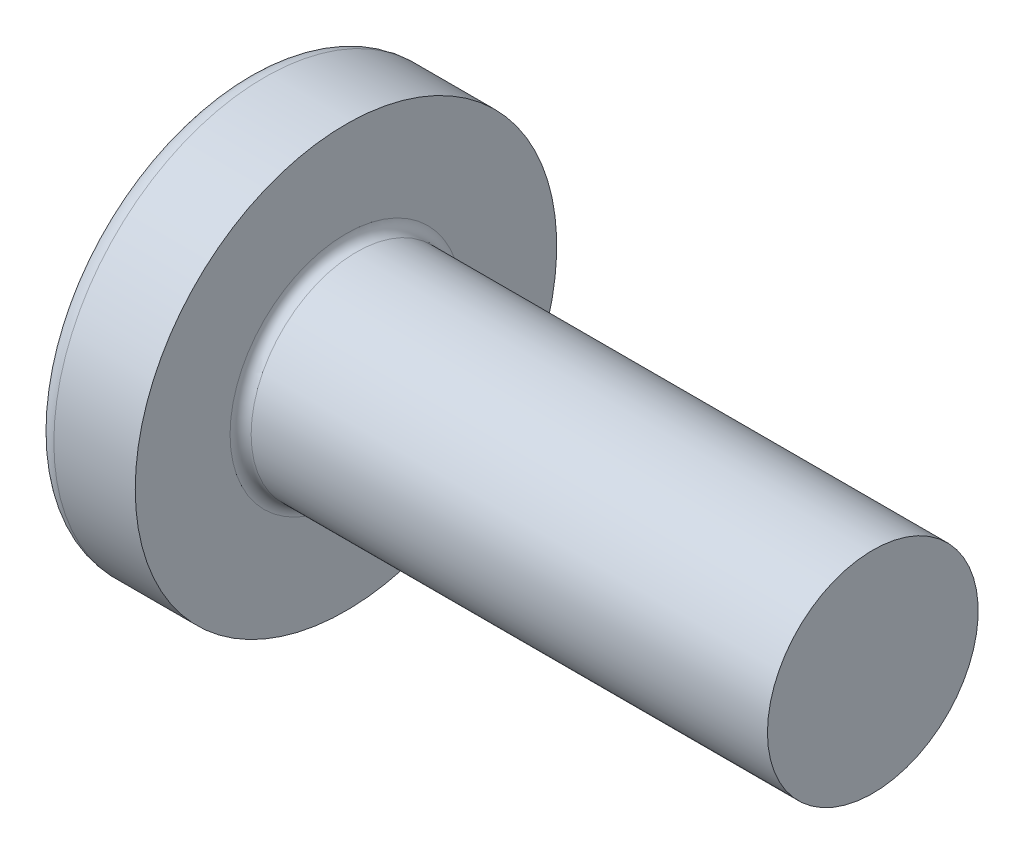
SolidWorks part; units mm, degrees
ref_plane "Plane1" through (0, 0, 0) normal (0, 0, 1) x (1, 0, 0)
ref_plane "Plane2" through (0, 0, 0) normal (0, 1, 0) x (1, 0, 0)
ref_plane "Plane3" through (0, 0, 0) normal (1, 0, 0) x (0, 0, -1)
sketch "BodySke" plane through (0, 0, 0) normal (0, 0, 1) x (1, 0, 0)
  line L0 (3.1, 2) -> (3.1, 4)
  line L1 (3.45, 6.35) -> (3.45, -3.175) construction
  line L2 (-25.4, 0) -> (127, 0) construction
  line L3 (13.1, 0) -> (0, 0)
  line L4 (3.1, 2) -> (13.1, 2)
  line L5 (13.1, 2) -> (13.1, 0)
  line L6 (1.5553, 4) -> (3.1, 4)
  line L8 (3.1, 6.35) -> (3.1, -3.175) construction
  arc A0 (1.2654, 3.8534) -> (0, 0) centre (6.5, 0) ccw
  arc A2 (1.2654, 3.8534) -> (1.5553, 4) centre (1.5553, 3.64) cw
  dimension "Head_crown_rad" = 6.5
  dimension "Head_fillet_rad" = 0.36
  dimension "Length" = 10
  dimension "Head_ht" = 3.1
  dimension "Head_dia" = 8
  dimension "Advance" = 0.7
  dimension "Thread_nom" = 10
  dimension "Diameter" = 4
revolve "Base-Revolve" add sketch "BodySke"
cosmetic thread "ThreadCosmetic"
fillet "Fillet1" radius 0.2 1 edges at (3.1, 0, 2)
sketch "Sketch3" plane through (0, 0, 0) normal (1, 0, 0) x (0, 0, -1)
  line L0 (0.515, -2.15) -> (-0.515, -2.15)
  line L1 (0.515, -2.15) -> (0.515, 2.15)
  line L2 (-0.515, 2.15) -> (0.515, 2.15)
  line L3 (-0.515, 2.15) -> (-0.515, -2.15)
  dimension "Cross_dia" = 4.3
  dimension "D1" = 2.15
  dimension "Cross_width" = 1.03
  dimension "D2" = 0.515
ref_plane "Plane4" through (2.34, 0, 0) normal (1, 0, 0) x (0, 0, -1)
sketch "Sketch4" plane through (2.34, 0, 0) normal (1, 0, 0) x (0, 0, -1)
  line L0 (0.515, -0.9833) -> (-0.515, -0.9833)
  line L1 (0.515, -0.9833) -> (0.515, 0.9833)
  line L2 (-0.515, 0.9833) -> (0.515, 0.9833)
  line L3 (-0.515, 0.9833) -> (-0.515, -0.9833)
  dimension "D1" = 1.03
  dimension "D2" = 1.9666
  dimension "D3" = 0.515
  dimension "D4" = 0.9833
loft "Recess" cut profiles "Sketch3", "Sketch4"
pattern_circular "RecPat" count 2 every 90 about axis through (0, 0, 0) along (1, 0, 0) of "Recess"
sketch "RecCorSke" plane through (0, 0, 0) normal (0, 0, 1) x (1, 0, 0)
  line L0 (-3.175, 0) -> (15.875, 0) construction
  line L1 (-25.4, 0) -> (127, 0) construction
  line L2 (0, 0) -> (0, 1.0146)
  line L3 (0, 1.0146) -> (2.34, 0.851)
  line L4 (2.34, 0.851) -> (2.6165, 0)
  line L5 (2.6165, 0) -> (0, 0)
  dimension "Diameter" = 1.702
  dimension "Depth" = 2.34
  dimension "Draft_angle" = 4
  dimension "Bottom_angle" = 18
revolve "RecessCore" cut sketch "RecCorSke" angle 360 about L0
sketch "ThdSchSke" plane through (0, 0, 0) normal (0, 0, 1) x (1, 0, 0)
  line L0 (4.5, -1.61) -> (4.2269, -2)
  line L1 (4.5, -1.61) -> (4.7731, -2)
  line L2 (4.7731, -2) -> (4.7731, -2.5)
  line L3 (-3.175, 0) -> (5.1513, 0) construction
  line L5 (4.7731, -2.5) -> (4.2269, -2.5)
  line L6 (4.2269, -2.5) -> (4.2269, -2)
  dimension "Diameter" = 4
  dimension "SideAngle" = 55
  dimension "VeeAngle" = 70
  dimension "Thread_minor" = 3.22
  dimension "Overcut" = 5
  dimension "Start" = 4.5
revolve "ThreadSchematic" [suppressed] cut sketch "ThdSchSke" angle 360 about L3
pattern_linear "ThdSchPat" [suppressed]
equation "\"D1@Sketch3\" = \"Cross_dia@Sketch3\" / 2"
equation "\"D2@Sketch3\" = \"Cross_width@Sketch3\" / 2"
equation "\"Depth@RecCorSke\" = \"Cross_depth@Plane4\""
equation "\"D1@Sketch4\" = \"Cross_width@Sketch3\""
equation "\"D2@Sketch4\" = \"Cross_dia@Sketch3\" - 2.0 * \"Cross_depth@Plane4\" * tan(26.5  * 0.017453292)"
equation "\"D3@Sketch4\" = \"D1@Sketch4\" / 2"
equation "\"D4@Sketch4\" = \"D2@Sketch4\" / 2"
equation "\"Thread_length@ThreadCosmetic\" = ((sgn( (\"Length@BodySke\" - \"Advance@BodySke\" * 2.0 ) - \"Thread_nom@BodySke\" )-1)*( (\"Length@BodySke\" - \"Advance@BodySke\" * 2.0 ) - \"Thread_nom@BodySke\" ))/-2+ \"Thread_nom@BodySke\""
equation "\"Thread_minor@ThdSchSke\" = \"Thread_minor@ThreadCosmetic\""
equation "\"Diameter@ThdSchSke\" = \"Diameter@BodySke\""
equation "\"Overcut@ThdSchSke\" = \"Diameter@BodySke\" * 1.25"
equation "\"Start@ThdSchSke\" = \"Head_ht@BodySke\" + \"Length@BodySke\" - \"Thread_length@ThreadCosmetic\"  '---Non-countersunk---"
equation "\"Num_threads@ThdSchPat\" = int( \"Thread_length@ThreadCosmetic\" / \"Advance@BodySke\" + 0.999 )  + 1"
equation "\"Advance@ThdSchPat\" = \"Thread_length@ThreadCosmetic\" /  (\"Num_threads@ThdSchPat\" - 1) 'relax it"
